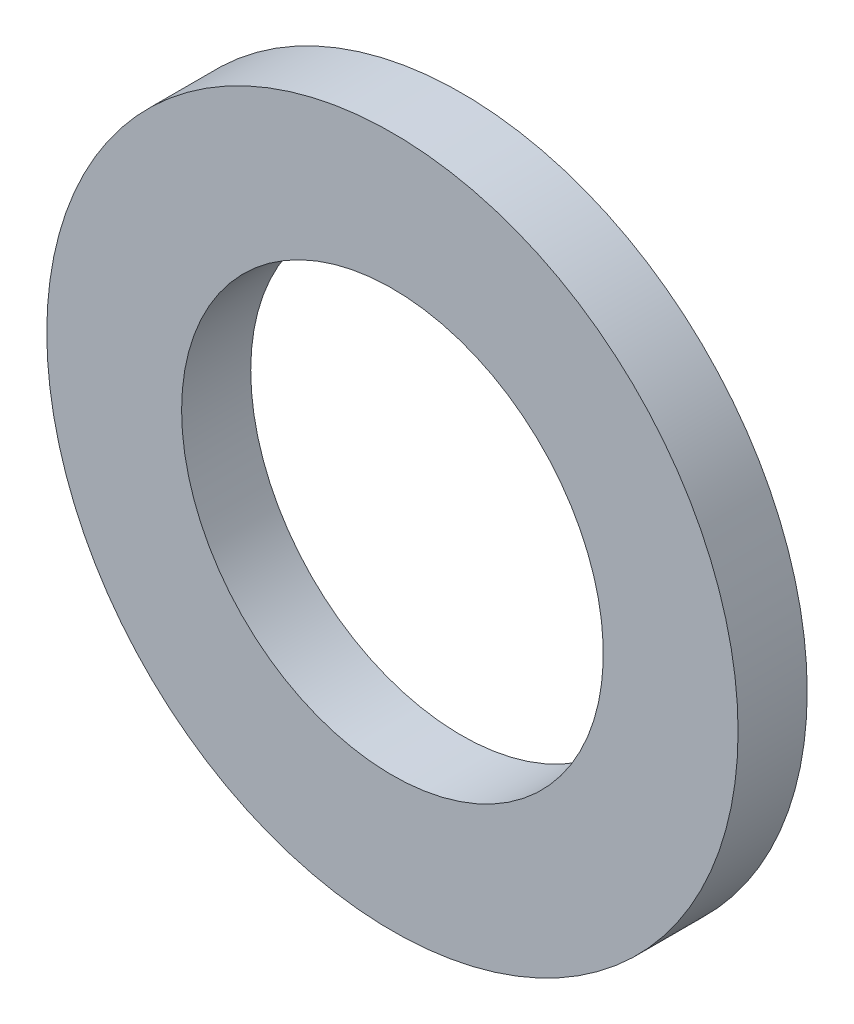
SolidWorks part; units mm, degrees
ref_plane "Front Plane" through (0, 0, 0) normal (0, 0, 1) x (1, 0, 0)
ref_plane "Top Plane" through (0, 0, 0) normal (0, 1, 0) x (1, 0, 0)
ref_plane "Right Plane" through (0, 0, 0) normal (1, 0, 0) x (0, 0, -1)
ref_plane "Plane1" through (0, 0, 0) normal (0, -1, 0) x (1, 0, 0)
sketch "Sketch1" plane through (0, 0, 0) normal (0, -1, 0) x (1, 0, 0)
  line L0 (2.5, -0.25) -> (2.5, 0.25)
  line L1 (2.5, 0.25) -> (1.525, 0.25)
  line L2 (1.525, 0.25) -> (1.525, -0.25)
  line L3 (1.525, -0.25) -> (2.5, -0.25)
  line L4 (0, 0.25) -> (0, -0.25) construction
  point P6 (0.193, -0.2071)
  dimension "D1" = 1.525
  dimension "D2" = 2.5
  dimension "D3" = 0.5
revolve "Revolve1" add sketch "Sketch1" angle 360 about L4
